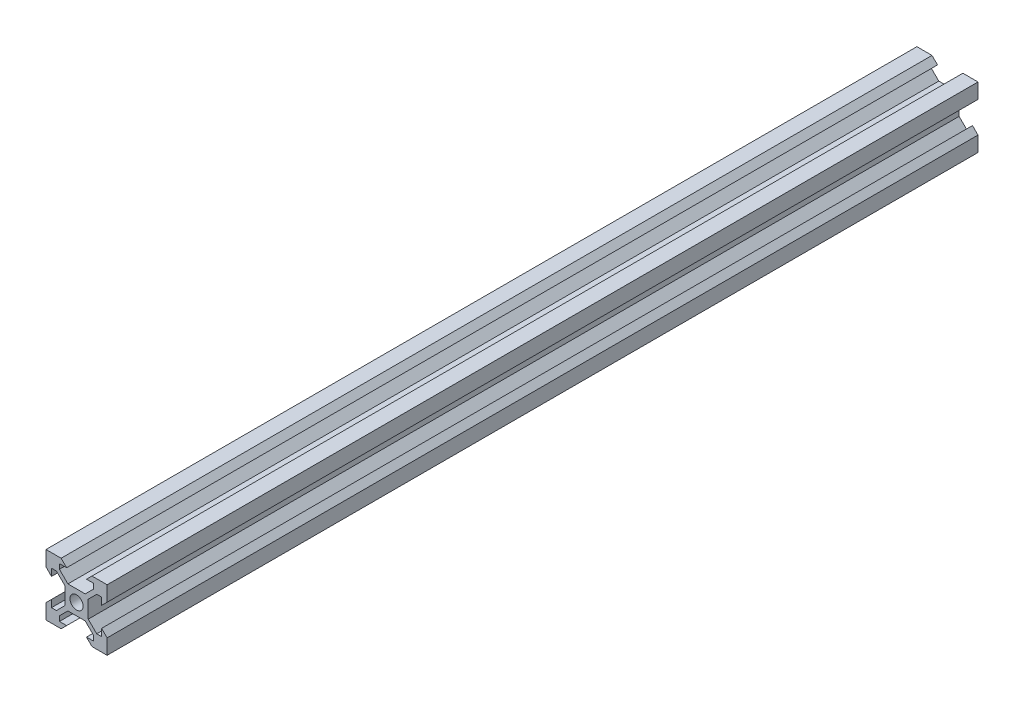
SolidWorks part; units mm, degrees
ref_plane "Alzado" through (0, 0, 0) normal (0, 0, 1) x (1, 0, 0)
ref_plane "Planta" through (0, 0, 0) normal (0, 1, 0) x (1, 0, 0)
ref_plane "Vista lateral" through (0, 0, 0) normal (1, 0, 0) x (0, 0, -1)
sketch "Croquis1" plane through (0, 0, 0) normal (0, 0, 1) x (1, 0, 0)
  line L0 (0, 0) -> (0, -20) construction
  line L2 (0, 0) -> (0, -0.5674)
  line L5 (6.175, -7.1649) -> (6.175, -12.8351)
  line L6 (7.1649, -13.825) -> (12.8351, -13.825)
  line L7 (13.825, -7.1649) -> (13.825, -12.8351)
  line L8 (7.1649, -6.175) -> (12.8351, -6.175)
  line L9 (6.175, -13.825) -> (13.825, -13.825) construction
  line L10 (13.825, -6.175) -> (13.825, -13.825) construction
  line L12 (10, -10) -> (32.1172, -10) construction
  line L13 (13.25, -18.2) -> (15.05, -20)
  line L14 (20, -20) -> (15.6, -20)
  line L15 (20, -20) -> (20, -15.6)
  line L16 (18.2, -15.6) -> (16.5899, -15.6)
  line L32 (15.6, -18.2) -> (15.6, -16.5899)
  line L33 (10, -10) -> (10, -23.2493) construction
  line L34 (4.4, -18.2) -> (4.4, -16.5899)
  line L35 (7.1649, -13.825) -> (4.4, -16.5899)
  line L36 (15.6, -18.2) -> (13.25, -18.2)
  line L38 (15.6, -20) -> (15.05, -20)
  line L40 (15.05, -20) -> (20, -20)
  line L41 (0, -20) -> (20, -20) construction
  line L42 (6.175, -12.8351) -> (3.4101, -15.6)
  line L43 (18.2, -13.25) -> (20, -15.05)
  line L44 (20, -20) -> (18.2, -20)
  line L45 (20, -20) -> (20, -15.05)
  line L48 (20, -15.05) -> (20, -20)
  line L49 (20, 0) -> (20, -20) construction
  line L50 (18.2, -15.6) -> (18.2, -13.25)
  line L51 (12.8351, -13.825) -> (15.6, -16.5899)
  line L52 (13.825, -12.8351) -> (16.5899, -15.6)
  line L53 (1.8, -15.6) -> (3.4101, -15.6)
  line L54 (1.8, -15.6) -> (1.8, -13.25)
  line L55 (1.8, -13.25) -> (0, -15.05)
  line L56 (0, 0) -> (20, 0) construction
  line L57 (0, -20) -> (0, -15.6)
  line L58 (0, -15.6) -> (0, -15.05)
  line L59 (0, -20) -> (4.4, -20)
  line L60 (0, -20) -> (4.95, -20)
  line L61 (6.75, -18.2) -> (4.95, -20)
  line L62 (4.4, -18.2) -> (6.75, -18.2)
  line L63 (1.8, -4.4) -> (3.4101, -4.4)
  line L64 (6.175, -7.1649) -> (3.4101, -4.4)
  line L65 (7.1649, -6.175) -> (4.4, -3.4101)
  line L66 (4.4, -1.8) -> (4.4, -3.4101)
  line L67 (4.4, -1.8) -> (6.75, -1.8)
  line L68 (6.75, -1.8) -> (4.95, 0)
  line L69 (0, 0) -> (4.4, 0)
  line L70 (4.4, 0) -> (4.95, 0)
  line L71 (0, 0) -> (0, -4.4)
  line L72 (0, 0) -> (0, -4.95)
  line L73 (1.8, -6.75) -> (0, -4.95)
  line L74 (1.8, -4.4) -> (1.8, -6.75)
  line L75 (15.6, -1.8) -> (15.6, -3.4101)
  line L76 (12.8351, -6.175) -> (15.6, -3.4101)
  line L77 (13.825, -7.1649) -> (16.5899, -4.4)
  line L78 (18.2, -4.4) -> (16.5899, -4.4)
  line L79 (18.2, -4.4) -> (18.2, -6.75)
  line L80 (18.2, -6.75) -> (20, -4.95)
  line L81 (20, 0) -> (20, -4.4)
  line L82 (20, -4.4) -> (20, -4.95)
  line L83 (20, 0) -> (15.6, 0)
  line L84 (20, 0) -> (15.05, 0)
  line L85 (13.25, -1.8) -> (15.05, 0)
  line L86 (15.6, -1.8) -> (13.25, -1.8)
  line L87 (6.175, -6.175) -> (13.825, -6.175) construction
  line L88 (6.175, -6.175) -> (6.175, -13.825) construction
  circle A0 centre (10, -10) radius 2.15
  point P69 (10, -10)
  dimension "D3" = 4.3
  dimension "D2" = 4
  dimension "D11" = 4.4
  dimension "D15" = 4.4
  dimension "D16" = 6.75
extrude "BoschBase" add sketch "Croquis1" along normal blind 285 contours L86 L75 L76 L8 L65 L66 L67 L68 L70 L69 L2 L71 L72 L73 L74 L63 L64 L5 L42 L53 L54 L55 L58 L57 L59 L60 L61 L62 L34 L35 L6 L51 L32 L36 L13 L38 L40 L14 L15 L45 L43 L50 L16 L52 L7 L77 L78 L79 L80 L82 L81
